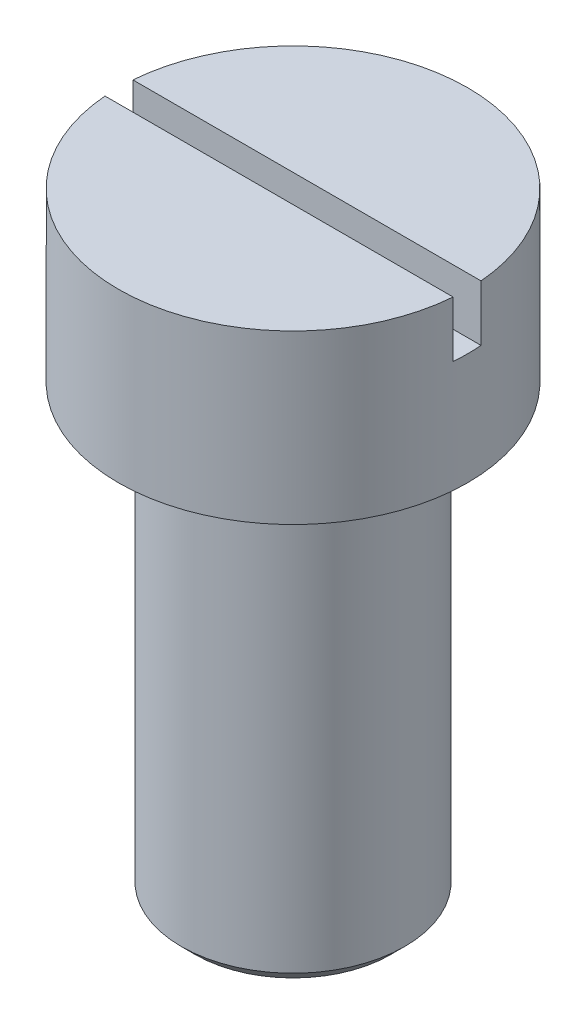
SolidWorks part; units mm, degrees
ref_plane "Front Plane" through (0, 0, 0) normal (0, 0, 1) x (1, 0, 0)
ref_plane "Top Plane" through (0, 0, 0) normal (0, 1, 0) x (1, 0, 0)
ref_plane "Right Plane" through (0, 0, 0) normal (1, 0, 0) x (0, 0, -1)
sketch "Sketch1" plane through (0, 0, 0) normal (0, 1, 0) x (1, 0, 0)
  circle A0 centre (0, 0) radius 12.5
extrude "Boss-Extrude1" add sketch "Sketch1" along normal blind 12
sketch "Sketch2" plane through (0, 0, 0) normal (0, -1, 0) x (1, 0, 0)
  circle A0 centre (0, 0) radius 8
extrude "Boss-Extrude2" add sketch "Sketch2" along normal blind 32
sketch "Sketch3" plane through (0, 0, 0) normal (1, 0, 0) x (0, 0, -1)
  line L0 (-1, 12) -> (-1, 8)
  line L1 (12.5, 12) -> (-12.5, 12) construction
  line L2 (-1, 8) -> (1, 8)
  line L3 (1, 8) -> (1, 12)
  dimension "D1" = 4
  dimension "D2" = 2
  dimension "D3" = 1
extrude "Cut-Extrude1" cut sketch "Sketch3" against normal through all both and the other way through all
chamfer "Chamfer1" distance 1 angle 45 1 edges at (0, -32, -8)
cosmetic thread "Cosmetic Thread1" parameters "D1"=25, "D2"=13.797
